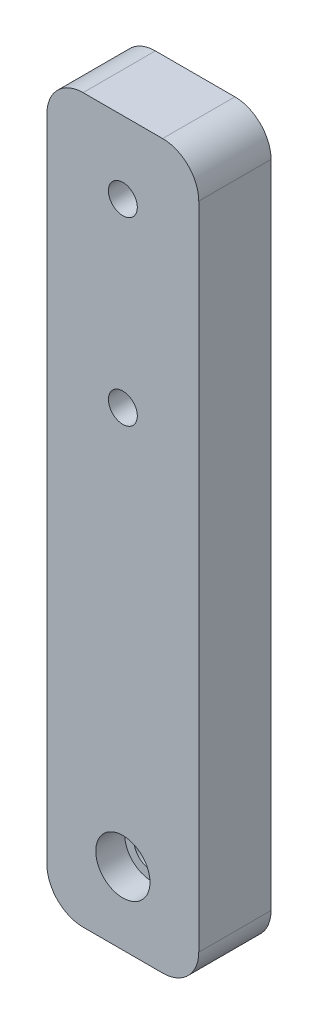
SolidWorks part; units mm, degrees
ref_plane "Plan de face" through (0, 0, 0) normal (0, 0, 1) x (1, 0, 0)
ref_plane "Plan de dessus" through (0, 0, 0) normal (0, 1, 0) x (1, 0, 0)
ref_plane "Plan de droite" through (0, 0, 0) normal (1, 0, 0) x (0, 0, -1)
sketch "Esquisse1" plane through (0, 0, 0) normal (0, 0, 1) x (1, 0, 0)
  line L1 (-8.2828, 10) -> (12.7172, 10)
  line L2 (-8.2828, 10) -> (-8.2828, -90)
  line L3 (-8.2828, -90) -> (12.7172, -90)
  line L4 (12.7172, 10) -> (12.7172, -90)
  dimension "D1" = 21
  dimension "D2" = 100
extrude "Boss.-Extru.1" add sketch "Esquisse1" along normal blind 10
sketch "Esquisse2" plane through (0, 0, 10) normal (0, 0, 1) x (1, 0, 0)
  line L0 (12.7172, 10) -> (-8.2828, 10) construction
  line L1 (-8.2828, -90) -> (12.7172, -90) construction
  circle A0 centre (2.2172, 0) radius 2
  circle A1 centre (2.2172, -25) radius 2
  circle A2 centre (2.2172, -80) radius 2.5
  point P9 (2.2172, 10)
  dimension "D1" = 4
  dimension "D2" = 5
  dimension "D3" = 25
  dimension "D4" = 10
  dimension "D5" = 10
extrude "Enlèv. mat.-Extru.1" cut sketch "Esquisse2" against normal up to vertex (10 mm away)
fillet "Congé1" radius 5 4 edges at (-8.2828, 10, 5) (12.7172, 10, 5) (-8.2828, -90, 5) (12.7172, -90, 5)
sketch "Esquisse3" plane through (0, 0, 0) normal (0, 0, -1) x (-1, 0, 0)
  line L0 (-7.7172, 10) -> (3.2828, 10) construction
  line L1 (-3.8049, 2.75) -> (-5.3926, 0)
  line L2 (-5.3926, 0) -> (-3.8049, -2.75)
  line L3 (-3.8049, -2.75) -> (-0.6295, -2.75)
  line L4 (-0.6295, -2.75) -> (0.9582, 0)
  line L5 (0.9582, 0) -> (-0.6295, 2.75)
  line L6 (-0.6295, 2.75) -> (-3.8049, 2.75)
  line L7 (-3.8049, -22.25) -> (-5.3926, -25)
  line L8 (-5.3926, -25) -> (-3.8049, -27.75)
  line L9 (-3.8049, -27.75) -> (-0.6295, -27.75)
  line L10 (-0.6295, -27.75) -> (0.9582, -25)
  line L11 (0.9582, -25) -> (-0.6295, -22.25)
  line L12 (-0.6295, -22.25) -> (-3.8049, -22.25)
  circle A0 centre (-2.2172, 0) radius 2.75 construction
  circle A1 centre (-2.2172, -25) radius 2.75 construction
  dimension "D1" = 5.5
extrude "Enlèv. mat.-Extru.2" cut sketch "Esquisse3" against normal blind 4
sketch "Esquisse4" plane through (0, 0, 10) normal (0, 0, 1) x (1, 0, 0)
  circle A0 centre (2.2172, -80) radius 3.75
  dimension "D1" = 7.5
extrude "Enlèv. mat.-Extru.4" cut sketch "Esquisse4" against normal blind 4 contours A0
